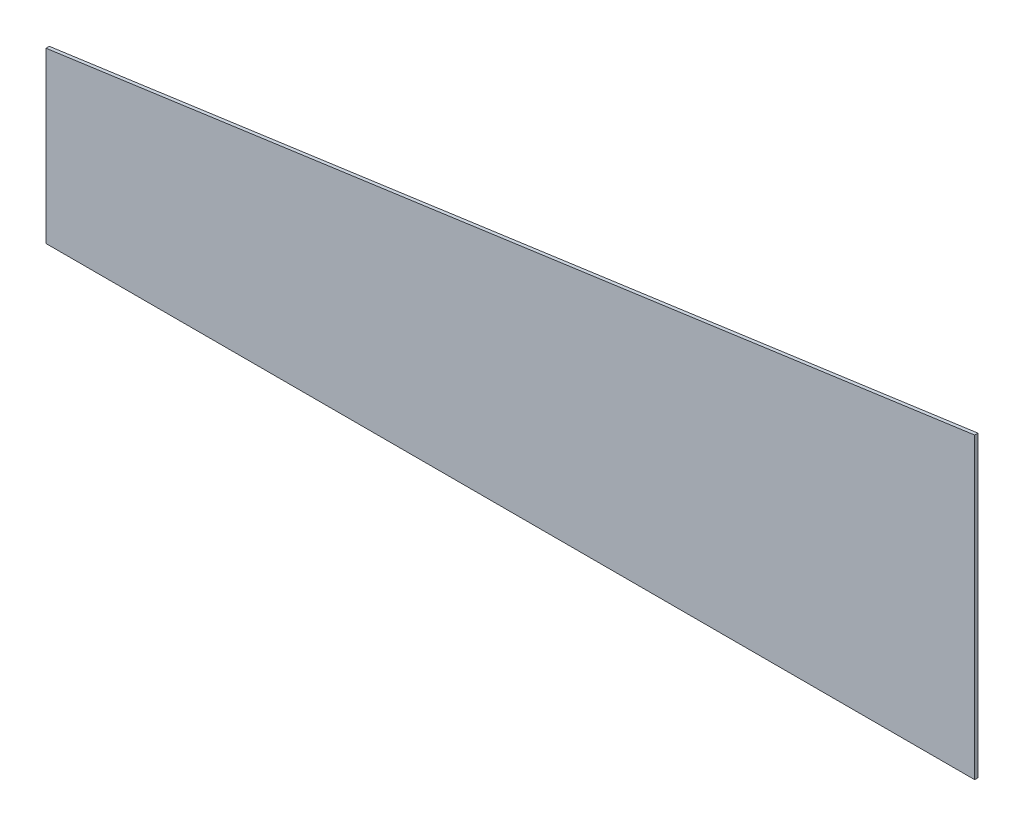
SolidWorks part; units mm, degrees
ref_plane "Front Plane" through (0, 0, 0) normal (0, 0, 1) x (1, 0, 0)
ref_plane "Top Plane" through (0, 0, 0) normal (0, 1, 0) x (1, 0, 0)
ref_plane "Right Plane" through (0, 0, 0) normal (1, 0, 0) x (0, 0, -1)
sketch "Sketch1" plane through (0, 0, 0) normal (0, 0, 1) x (1, 0, 0)
  line L0 (0, 0) -> (-280, 0)
  line L1 (-280, 0) -> (-280, 51)
  line L2 (-280, 51) -> (0, 90)
  line L3 (0, 90) -> (0, 0)
  point P3 (0, 0)
  point P7 (0, 0)
  point P8 (0, 1.5121)
  dimension "D1" = 280
  dimension "D2" = 51
  dimension "D3" = 90
extrude "Boss-Extrude1" add sketch "Sketch1" along normal blind 1 contours L2 L3 L0 L1
